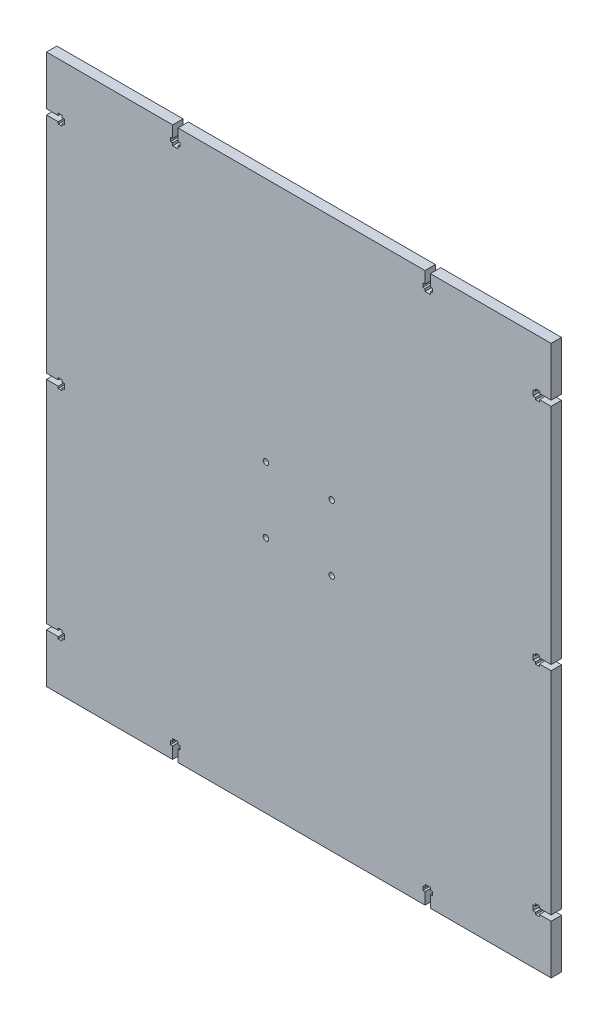
SolidWorks part; units mm, degrees
material "Клен"
ref_plane "Спереди" through (0, 0, 0) normal (0, 0, 1) x (1, 0, 0)
ref_plane "Сверху" through (0, 0, 0) normal (0, 1, 0) x (1, 0, 0)
ref_plane "Справа" through (0, 0, 0) normal (1, 0, 0) x (0, 0, -1)
sketch "Эскиз1" plane through (0, 0, 0) normal (0, 0, 1) x (1, 0, 0)
  line L0 (-142.6276, 165.1762) -> (-69.6276, 165.1762)
  line L5 (-142.6276, 165.1762) -> (-142.6276, 136.7262)
  line L6 (-142.6276, -152.8238) -> (-69.6276, -152.8238)
  line L7 (149.3724, 165.1762) -> (149.3724, 136.7262)
  line L8 (3.3724, 203.8374) -> (3.3724, -203.8374) construction
  line L9 (196.2616, 4.2262) -> (-196.2616, 4.2262) construction
  line L10 (-191.5634, 135.1762) -> (196.2616, 135.1762) construction
  line L11 (-191.5634, -124.3738) -> (186.5064, -124.3738) construction
  line L12 (-142.6276, -124.3738) -> (-142.6276, -152.8238)
  line L13 (-69.6276, 203.8374) -> (-69.6276, -203.8374) construction
  line L14 (76.3724, 203.8374) -> (76.3724, -203.8374) construction
  line L15 (-66.5276, 165.1762) -> (76.3724, 165.1762)
  line L16 (79.4724, 165.1762) -> (149.3724, 165.1762)
  line L17 (-66.5276, -152.8238) -> (76.3724, -152.8238)
  line L18 (79.4724, -152.8238) -> (149.3724, -152.8238)
  line L19 (196.2616, 136.7262) -> (-191.5634, 136.7262) construction
  line L20 (142.5724, 136.7262) -> (142.5724, 137.9262)
  line L21 (140.3724, 132.4262) -> (142.5724, 132.4262)
  line L22 (140.3724, 136.7262) -> (138.8724, 136.7262)
  line L23 (142.5724, 137.9262) -> (140.3724, 137.9262)
  line L24 (149.3724, 136.7262) -> (142.5724, 136.7262)
  line L25 (138.8724, 133.6262) -> (140.3724, 133.6262)
  line L26 (79.4724, 158.3762) -> (79.4724, 165.1762)
  line L27 (79.4724, 156.1762) -> (80.6724, 156.1762)
  line L28 (76.3724, 154.6762) -> (79.4724, 154.6762)
  line L29 (79.4724, 154.6762) -> (79.4724, 156.1762)
  line L30 (76.3724, 165.1762) -> (76.3724, 158.3762)
  line L31 (76.3724, 158.3762) -> (75.1724, 158.3762)
  line L32 (80.6724, 156.1762) -> (80.6724, 158.3762)
  line L33 (75.1724, 158.3762) -> (75.1724, 156.1762)
  line L34 (80.6724, 158.3762) -> (79.4724, 158.3762)
  line L35 (75.1724, 156.1762) -> (76.3724, 156.1762)
  line L36 (76.3724, 156.1762) -> (76.3724, 154.6762)
  line L37 (-66.5276, 158.3762) -> (-66.5276, 165.1762)
  line L38 (-66.5276, 156.1762) -> (-65.3276, 156.1762)
  line L39 (-69.6276, 154.6762) -> (-66.5276, 154.6762)
  line L40 (-66.5276, 154.6762) -> (-66.5276, 156.1762)
  line L41 (-69.6276, 165.1762) -> (-69.6276, 158.3762)
  line L42 (-69.6276, 158.3762) -> (-70.8276, 158.3762)
  line L43 (-65.3276, 156.1762) -> (-65.3276, 158.3762)
  line L44 (-70.8276, 158.3762) -> (-70.8276, 156.1762)
  line L45 (-65.3276, 158.3762) -> (-66.5276, 158.3762)
  line L46 (-70.8276, 156.1762) -> (-69.6276, 156.1762)
  line L47 (-69.6276, 156.1762) -> (-69.6276, 154.6762)
  line L48 (-69.6276, -143.8238) -> (-69.6276, -142.3238)
  line L49 (-70.8276, -143.8238) -> (-69.6276, -143.8238)
  line L50 (-65.3276, -146.0238) -> (-66.5276, -146.0238)
  line L51 (-70.8276, -146.0238) -> (-70.8276, -143.8238)
  line L52 (-65.3276, -143.8238) -> (-65.3276, -146.0238)
  line L53 (-69.6276, -146.0238) -> (-70.8276, -146.0238)
  line L54 (-69.6276, -152.8238) -> (-69.6276, -146.0238)
  line L55 (-66.5276, -142.3238) -> (-66.5276, -143.8238)
  line L56 (-69.6276, -142.3238) -> (-66.5276, -142.3238)
  line L57 (-66.5276, -143.8238) -> (-65.3276, -143.8238)
  line L58 (-66.5276, -146.0238) -> (-66.5276, -152.8238)
  line L59 (76.3724, -143.8238) -> (76.3724, -142.3238)
  line L60 (75.1724, -143.8238) -> (76.3724, -143.8238)
  line L61 (80.6724, -146.0238) -> (79.4724, -146.0238)
  line L62 (75.1724, -146.0238) -> (75.1724, -143.8238)
  line L63 (80.6724, -143.8238) -> (80.6724, -146.0238)
  line L64 (76.3724, -146.0238) -> (75.1724, -146.0238)
  line L65 (76.3724, -152.8238) -> (76.3724, -146.0238)
  line L66 (79.4724, -142.3238) -> (79.4724, -143.8238)
  line L67 (76.3724, -142.3238) -> (79.4724, -142.3238)
  line L68 (79.4724, -143.8238) -> (80.6724, -143.8238)
  line L69 (79.4724, -146.0238) -> (79.4724, -152.8238)
  line L70 (142.5724, 132.4262) -> (142.5724, 133.6262)
  line L71 (142.5724, 133.6262) -> (149.3724, 133.6262)
  line L72 (138.8724, 136.7262) -> (138.8724, 133.6262)
  line L73 (140.3724, 137.9262) -> (140.3724, 136.7262)
  line L74 (140.3724, 133.6262) -> (140.3724, 132.4262)
  line L75 (149.3724, 132.0762) -> (149.3724, 133.6262)
  line L76 (142.5724, -121.2738) -> (142.5724, -120.0738)
  line L77 (142.5724, -124.3738) -> (149.3724, -124.3738)
  line L78 (138.8724, -121.2738) -> (138.8724, -124.3738)
  line L79 (140.3724, -120.0738) -> (140.3724, -121.2738)
  line L80 (140.3724, -121.2738) -> (138.8724, -121.2738)
  line L81 (138.8724, -124.3738) -> (140.3724, -124.3738)
  line L82 (149.3724, -121.2738) -> (142.5724, -121.2738)
  line L83 (142.5724, -120.0738) -> (140.3724, -120.0738)
  line L84 (140.3724, -124.3738) -> (140.3724, -125.5738)
  line L85 (140.3724, -125.5738) -> (142.5724, -125.5738)
  line L86 (142.5724, -125.5738) -> (142.5724, -124.3738)
  line L87 (149.3724, -124.3738) -> (149.3724, -152.8238)
  line L88 (-133.6276, 133.6262) -> (-133.6276, 132.4262)
  line L89 (-133.6276, 137.9262) -> (-133.6276, 136.7262)
  line L90 (-132.1276, 136.7262) -> (-132.1276, 133.6262)
  line L91 (-135.8276, 133.6262) -> (-142.6276, 133.6262)
  line L92 (-135.8276, 132.4262) -> (-135.8276, 133.6262)
  line L93 (-132.1276, 133.6262) -> (-133.6276, 133.6262)
  line L94 (-142.6276, 136.7262) -> (-135.8276, 136.7262)
  line L95 (-135.8276, 137.9262) -> (-133.6276, 137.9262)
  line L96 (-133.6276, 136.7262) -> (-132.1276, 136.7262)
  line L97 (-133.6276, 132.4262) -> (-135.8276, 132.4262)
  line L98 (-135.8276, 136.7262) -> (-135.8276, 137.9262)
  line L99 (-135.8276, -125.5738) -> (-135.8276, -124.3738)
  line L100 (-133.6276, -125.5738) -> (-135.8276, -125.5738)
  line L101 (-133.6276, -124.3738) -> (-133.6276, -125.5738)
  line L102 (-135.8276, -120.0738) -> (-133.6276, -120.0738)
  line L103 (-142.6276, -121.2738) -> (-135.8276, -121.2738)
  line L104 (-132.1276, -124.3738) -> (-133.6276, -124.3738)
  line L105 (-133.6276, -121.2738) -> (-132.1276, -121.2738)
  line L106 (-133.6276, -120.0738) -> (-133.6276, -121.2738)
  line L107 (-132.1276, -121.2738) -> (-132.1276, -124.3738)
  line L108 (-135.8276, -124.3738) -> (-142.6276, -124.3738)
  line L109 (-135.8276, -121.2738) -> (-135.8276, -120.0738)
  line L110 (149.3724, 132.0762) -> (149.3724, 4.2262)
  line L111 (138.8724, 4.2262) -> (138.8724, 1.1262)
  line L112 (138.8724, 1.1262) -> (140.3724, 1.1262)
  line L113 (140.3724, 4.2262) -> (138.8724, 4.2262)
  line L114 (142.5724, 1.1262) -> (149.3724, 1.1262)
  line L115 (140.3724, -0.0738) -> (142.5724, -0.0738)
  line L116 (142.5724, -0.0738) -> (142.5724, 1.1262)
  line L117 (142.5724, 5.4262) -> (140.3724, 5.4262)
  line L118 (140.3724, 5.4262) -> (140.3724, 4.2262)
  line L119 (149.3724, 4.2262) -> (142.5724, 4.2262)
  line L120 (142.5724, 4.2262) -> (142.5724, 5.4262)
  line L121 (140.3724, 1.1262) -> (140.3724, -0.0738)
  line L122 (149.3724, 1.1262) -> (149.3724, -121.2738)
  line L123 (-133.6276, 1.1262) -> (-133.6276, -0.0738)
  line L124 (-135.8276, 4.2262) -> (-135.8276, 5.4262)
  line L125 (-142.6276, 4.2262) -> (-135.8276, 4.2262)
  line L126 (-133.6276, 5.4262) -> (-133.6276, 4.2262)
  line L127 (-135.8276, 5.4262) -> (-133.6276, 5.4262)
  line L128 (-135.8276, -0.0738) -> (-135.8276, 1.1262)
  line L129 (-133.6276, -0.0738) -> (-135.8276, -0.0738)
  line L130 (-135.8276, 1.1262) -> (-142.6276, 1.1262)
  line L131 (-133.6276, 4.2262) -> (-132.1276, 4.2262)
  line L132 (-132.1276, 1.1262) -> (-133.6276, 1.1262)
  line L133 (-132.1276, 4.2262) -> (-132.1276, 1.1262)
  line L134 (-142.6276, 133.6262) -> (-142.6276, 4.2262)
  line L135 (-142.6276, -121.2738) -> (-142.6276, 1.1262)
  line L136 (-31.5144, 23.2262) -> (33.277, 23.2262) construction
  line L137 (22.3724, 48.9126) -> (22.3724, 13.4316) construction
  circle A0 centre (22.3724, 23.2262) radius 1.6
  circle A1 centre (-15.6276, 23.2262) radius 1.6
  circle A2 centre (22.3724, -14.7738) radius 1.6
  circle A3 centre (-15.6276, -14.7738) radius 1.6
  dimension "D11" = 3.2
  dimension "D1" = 292
  dimension "D2" = 318
  dimension "D3" = 30
  dimension "D4" = 73
  dimension "D5" = 73
  dimension "D6" = 28.45
  dimension "D7" = 28.45
  dimension "D8" = 160.95
  dimension "D9" = 19
  dimension "D10" = 19
extrude "Бобышка-Вытянуть1" add sketch "Эскиз1" along normal blind 6
